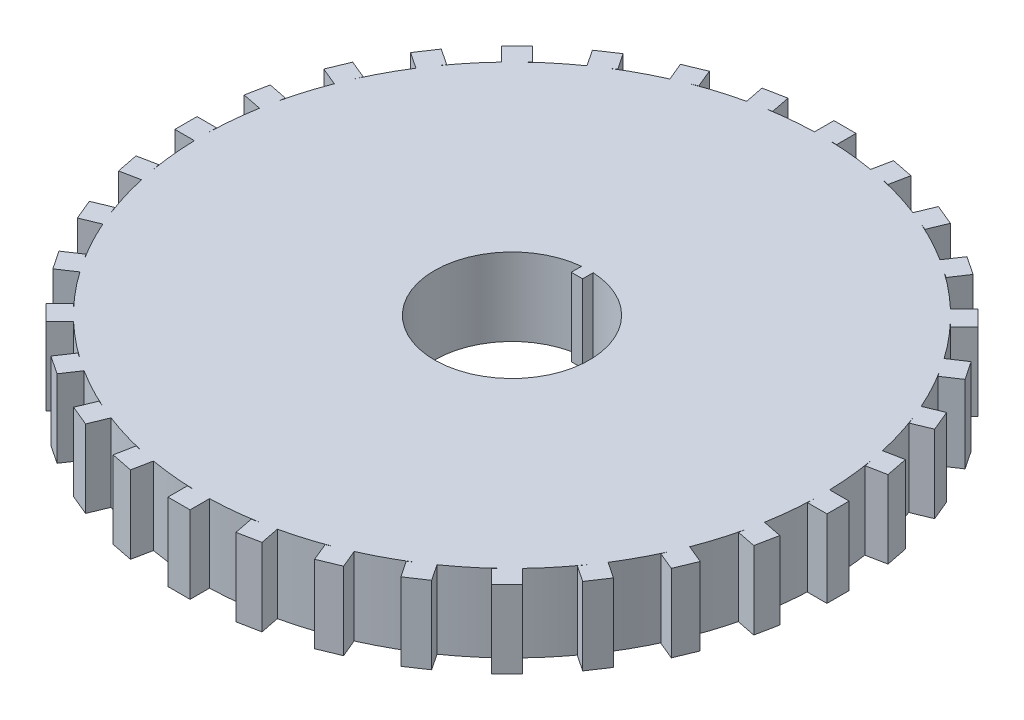
SolidWorks part; units mm, degrees
ref_plane "Front Plane" through (0, 0, 0) normal (0, 0, 1) x (1, 0, 0)
ref_plane "Top Plane" through (0, 0, 0) normal (0, 1, 0) x (1, 0, 0)
ref_plane "Right Plane" through (0, 0, 0) normal (1, 0, 0) x (0, 0, -1)
sketch "Sketch1" plane through (0, 0, 0) normal (0, 1, 0) x (1, 0, 0)
  line L0 (-0.6217, 6.3195) -> (-0.6217, 5.475)
  line L1 (-0.6217, 5.475) -> (0.3083, 5.475)
  line L2 (0.3083, 5.475) -> (0.3083, 6.3425)
  line L3 (4.6554, 26.5907) -> (6.4346, 26.2368)
  line L4 (-0.6217, 25.3924) -> (1.1924, 25.3924)
  line L5 (-0.6217, 25.3924) -> (-0.6217, 26.988)
  line L6 (-0.6217, 26.988) -> (1.1924, 26.988)
  line L7 (1.1924, 25.3924) -> (1.1924, 26.988)
  line L8 (4.3441, 25.0258) -> (4.6554, 26.5907)
  line L9 (6.1233, 24.6719) -> (6.4346, 26.2368)
  line L10 (4.3441, 25.0258) -> (6.1233, 24.6719)
  line L11 (9.7535, 25.1715) -> (11.4295, 24.4773)
  line L12 (9.1429, 23.6974) -> (9.7535, 25.1715)
  line L13 (10.8189, 23.0032) -> (11.4295, 24.4773)
  line L14 (9.1429, 23.6974) -> (10.8189, 23.0032)
  line L15 (14.4768, 22.7851) -> (15.9852, 21.7772)
  line L16 (13.5904, 21.4584) -> (14.4768, 22.7851)
  line L17 (15.0987, 20.4505) -> (15.9852, 21.7772)
  line L18 (13.5904, 21.4584) -> (15.0987, 20.4505)
  line L19 (18.6438, 19.523) -> (19.9265, 18.2402)
  line L20 (17.5155, 18.3947) -> (18.6438, 19.523)
  line L21 (18.7983, 17.112) -> (19.9265, 18.2402)
  line L22 (17.5155, 18.3947) -> (18.7983, 17.112)
  line L23 (22.0943, 15.5106) -> (23.1021, 14.0023)
  line L24 (20.7676, 14.6242) -> (22.0943, 15.5106)
  line L25 (21.7755, 13.1158) -> (23.1021, 14.0023)
  line L26 (20.7676, 14.6242) -> (21.7755, 13.1158)
  line L27 (24.6957, 10.9022) -> (25.39, 9.2262)
  line L28 (23.2216, 10.2916) -> (24.6957, 10.9022)
  line L29 (23.9158, 8.6156) -> (25.39, 9.2262)
  line L30 (23.2216, 10.2916) -> (23.9158, 8.6156)
  line L31 (26.3481, 5.8748) -> (26.702, 4.0956)
  line L32 (24.7832, 5.5635) -> (26.3481, 5.8748)
  line L33 (25.1371, 3.7843) -> (26.702, 4.0956)
  line L34 (24.7832, 5.5635) -> (25.1371, 3.7843)
  line L35 (26.988, 0.6217) -> (26.988, -1.1924)
  line L36 (25.3924, 0.6217) -> (26.988, 0.6217)
  line L37 (25.3924, -1.1924) -> (26.988, -1.1924)
  line L38 (25.3924, 0.6217) -> (25.3924, -1.1924)
  line L39 (26.5907, -4.6554) -> (26.2368, -6.4346)
  line L40 (25.0258, -4.3441) -> (26.5907, -4.6554)
  line L41 (24.6719, -6.1233) -> (26.2368, -6.4346)
  line L42 (25.0258, -4.3441) -> (24.6719, -6.1233)
  line L43 (25.1715, -9.7535) -> (24.4773, -11.4295)
  line L44 (23.6974, -9.1429) -> (25.1715, -9.7535)
  line L45 (23.0032, -10.8189) -> (24.4773, -11.4295)
  line L46 (23.6974, -9.1429) -> (23.0032, -10.8189)
  line L47 (22.7851, -14.4768) -> (21.7772, -15.9852)
  line L48 (21.4584, -13.5904) -> (22.7851, -14.4768)
  line L49 (20.4505, -15.0987) -> (21.7772, -15.9852)
  line L50 (21.4584, -13.5904) -> (20.4505, -15.0987)
  line L51 (19.523, -18.6438) -> (18.2402, -19.9265)
  line L52 (18.3947, -17.5155) -> (19.523, -18.6438)
  line L53 (17.112, -18.7983) -> (18.2402, -19.9265)
  line L54 (18.3947, -17.5155) -> (17.112, -18.7983)
  line L55 (15.5106, -22.0943) -> (14.0023, -23.1021)
  line L56 (14.6242, -20.7676) -> (15.5106, -22.0943)
  line L57 (13.1158, -21.7755) -> (14.0023, -23.1021)
  line L58 (14.6242, -20.7676) -> (13.1158, -21.7755)
  line L59 (10.9022, -24.6957) -> (9.2262, -25.39)
  line L60 (10.2916, -23.2216) -> (10.9022, -24.6957)
  line L61 (8.6156, -23.9158) -> (9.2262, -25.39)
  line L62 (10.2916, -23.2216) -> (8.6156, -23.9158)
  line L63 (5.8748, -26.3481) -> (4.0956, -26.702)
  line L64 (5.5635, -24.7832) -> (5.8748, -26.3481)
  line L65 (3.7843, -25.1371) -> (4.0956, -26.702)
  line L66 (5.5635, -24.7832) -> (3.7843, -25.1371)
  line L67 (0.6217, -26.988) -> (-1.1924, -26.988)
  line L68 (0.6217, -25.3924) -> (0.6217, -26.988)
  line L69 (-1.1924, -25.3924) -> (-1.1924, -26.988)
  line L70 (0.6217, -25.3924) -> (-1.1924, -25.3924)
  line L71 (-4.6554, -26.5907) -> (-6.4346, -26.2368)
  line L72 (-4.3441, -25.0258) -> (-4.6554, -26.5907)
  line L73 (-6.1233, -24.6719) -> (-6.4346, -26.2368)
  line L74 (-4.3441, -25.0258) -> (-6.1233, -24.6719)
  line L75 (-9.7535, -25.1715) -> (-11.4295, -24.4773)
  line L76 (-9.1429, -23.6974) -> (-9.7535, -25.1715)
  line L77 (-10.8189, -23.0032) -> (-11.4295, -24.4773)
  line L78 (-9.1429, -23.6974) -> (-10.8189, -23.0032)
  line L79 (-14.4768, -22.7851) -> (-15.9852, -21.7772)
  line L80 (-13.5904, -21.4584) -> (-14.4768, -22.7851)
  line L81 (-15.0987, -20.4505) -> (-15.9852, -21.7772)
  line L82 (-13.5904, -21.4584) -> (-15.0987, -20.4505)
  line L83 (-18.6438, -19.523) -> (-19.9265, -18.2402)
  line L84 (-17.5155, -18.3947) -> (-18.6438, -19.523)
  line L85 (-18.7983, -17.112) -> (-19.9265, -18.2402)
  line L86 (-17.5155, -18.3947) -> (-18.7983, -17.112)
  line L87 (-22.0943, -15.5106) -> (-23.1021, -14.0023)
  line L88 (-20.7676, -14.6242) -> (-22.0943, -15.5106)
  line L89 (-21.7755, -13.1158) -> (-23.1021, -14.0023)
  line L90 (-20.7676, -14.6242) -> (-21.7755, -13.1158)
  line L91 (-24.6957, -10.9022) -> (-25.39, -9.2262)
  line L92 (-23.2216, -10.2916) -> (-24.6957, -10.9022)
  line L93 (-23.9158, -8.6156) -> (-25.39, -9.2262)
  line L94 (-23.2216, -10.2916) -> (-23.9158, -8.6156)
  line L95 (-26.3481, -5.8748) -> (-26.702, -4.0956)
  line L96 (-24.7832, -5.5635) -> (-26.3481, -5.8748)
  line L97 (-25.1371, -3.7843) -> (-26.702, -4.0956)
  line L98 (-24.7832, -5.5635) -> (-25.1371, -3.7843)
  line L99 (-26.988, -0.6217) -> (-26.988, 1.1924)
  line L100 (-25.3924, -0.6217) -> (-26.988, -0.6217)
  line L101 (-25.3924, 1.1924) -> (-26.988, 1.1924)
  line L102 (-25.3924, -0.6217) -> (-25.3924, 1.1924)
  line L103 (-26.5907, 4.6554) -> (-26.2368, 6.4346)
  line L104 (-25.0258, 4.3441) -> (-26.5907, 4.6554)
  line L105 (-24.6719, 6.1233) -> (-26.2368, 6.4346)
  line L106 (-25.0258, 4.3441) -> (-24.6719, 6.1233)
  line L107 (-25.1715, 9.7535) -> (-24.4773, 11.4295)
  line L108 (-23.6974, 9.1429) -> (-25.1715, 9.7535)
  line L109 (-23.0032, 10.8189) -> (-24.4773, 11.4295)
  line L110 (-23.6974, 9.1429) -> (-23.0032, 10.8189)
  line L111 (-22.7851, 14.4768) -> (-21.7772, 15.9852)
  line L112 (-21.4584, 13.5904) -> (-22.7851, 14.4768)
  line L113 (-20.4505, 15.0987) -> (-21.7772, 15.9852)
  line L114 (-21.4584, 13.5904) -> (-20.4505, 15.0987)
  line L115 (-19.523, 18.6438) -> (-18.2402, 19.9265)
  line L116 (-18.3947, 17.5155) -> (-19.523, 18.6438)
  line L117 (-17.112, 18.7983) -> (-18.2402, 19.9265)
  line L118 (-18.3947, 17.5155) -> (-17.112, 18.7983)
  line L119 (-15.5106, 22.0943) -> (-14.0023, 23.1021)
  line L120 (-14.6242, 20.7676) -> (-15.5106, 22.0943)
  line L121 (-13.1158, 21.7755) -> (-14.0023, 23.1021)
  line L122 (-14.6242, 20.7676) -> (-13.1158, 21.7755)
  line L123 (-10.9022, 24.6957) -> (-9.2262, 25.39)
  line L124 (-10.2916, 23.2216) -> (-10.9022, 24.6957)
  line L125 (-8.6156, 23.9158) -> (-9.2262, 25.39)
  line L126 (-10.2916, 23.2216) -> (-8.6156, 23.9158)
  line L127 (-5.8748, 26.3481) -> (-4.0956, 26.702)
  line L128 (-5.5635, 24.7832) -> (-5.8748, 26.3481)
  line L129 (-3.7843, 25.1371) -> (-4.0956, 26.702)
  line L130 (-5.5635, 24.7832) -> (-3.7843, 25.1371)
  arc A0 (-0.6217, 6.3195) -> (0.3083, 6.3425) centre (0, 0) ccw
  circle A1 centre (0, 0) radius 25.4
  point P137 (0, 0)
  dimension "D1" = 12.7
  dimension "D2" = 50.8
  dimension "D3" = 32
extrude "Boss-Extrude1" add sketch "Sketch1" along normal blind 6.35 contours A1 L82 L81 L79 L80 | A1 L90 L89 L87 L88 | A1 L86 L85 L83 L84 | A1 L74 L73 L71 L72 | L0 A0 L2 L1 | A1 L58 L57 L55 L56 | A1 L62 L61 L59 L60 | A1 L54 L53 L51 L52 | A1 L50 L49 L47 L48 | A1 L46 L45 L43 L44 | A1 L38 L37 L35 L36 | A1 L18 L17 L15 L16 | A1 L22 L21 L19 L20 | A1 L4 L7 L6 L5 | A1 L10 L9 L3 L8 | A1 L14 L13 L11 L12 | A1 L130 L129 L127 L128 | A1 L126 L125 L123 L124 | A1 L122 L121 L119 L120 | A1 L118 L117 L115 L116 | A1 L114 L113 L111 L112 | A1 L110 L109 L107 L108 | A1 L106 L105 L103 L104 | A1 L102 L101 L99 L100 | A1 L98 L97 L95 L96 | A1 L94 L93 L91 L92 | A1 L66 L65 L63 L64 | L78 L77 L75 L76 | L70 L69 L67 L68 | L39 L41 L42 L40 | L31 L33 L34 L32 | L28 L27 L29 L30 | L24 L23 L25 L26
